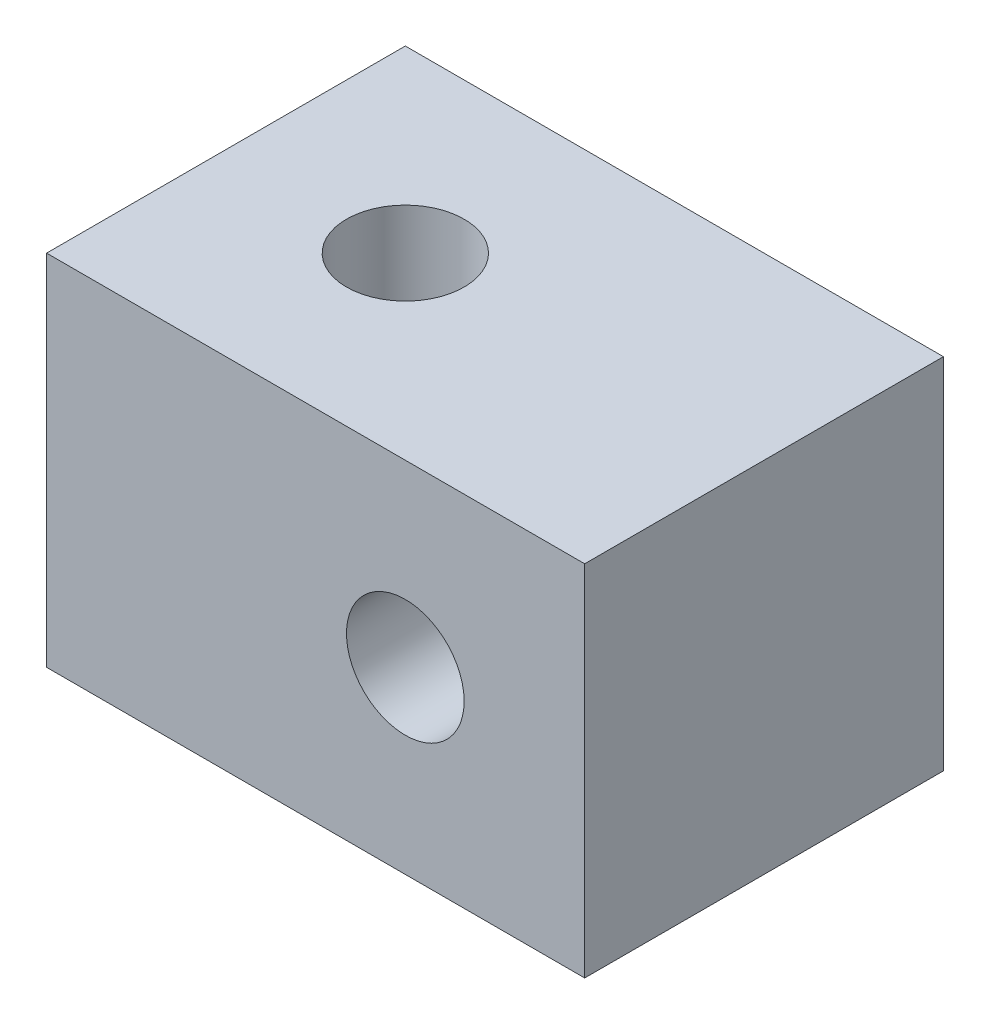
SolidWorks part; units mm, degrees
ref_plane "Front Plane" through (0, 0, 0) normal (0, 0, 1) x (1, 0, 0)
ref_plane "Top Plane" through (0, 0, 0) normal (0, 1, 0) x (1, 0, 0)
ref_plane "Right Plane" through (0, 0, 0) normal (1, 0, 0) x (0, 0, -1)
sketch "Sketch1" plane through (0, 0, 0) normal (0, 1, 0) x (1, 0, 0)
  line L0 (0, 0) -> (0, 12.7)
  line L1 (0, 12.7) -> (19.05, 12.7)
  line L2 (19.05, 12.7) -> (19.05, 0)
  line L3 (19.05, 0) -> (0, 0)
  line L4 (0, 6.35) -> (6.35, 6.35) construction
  circle A0 centre (6.35, 6.35) radius 2.0828
extrude "Boss-Extrude1" add sketch "Sketch1" along normal blind 12.7
sketch "Sketch2" plane through (0, 0, 0) normal (0, 0, 1) x (1, 0, 0)
  line L0 (19.05, 6.35) -> (12.7, 6.35) construction
  line L1 (19.05, 12.7) -> (19.05, 0) construction
  circle A0 centre (12.7, 6.35) radius 2.0828
extrude "Cut-Extrude1" cut sketch "Sketch2" against normal blind 12.7
